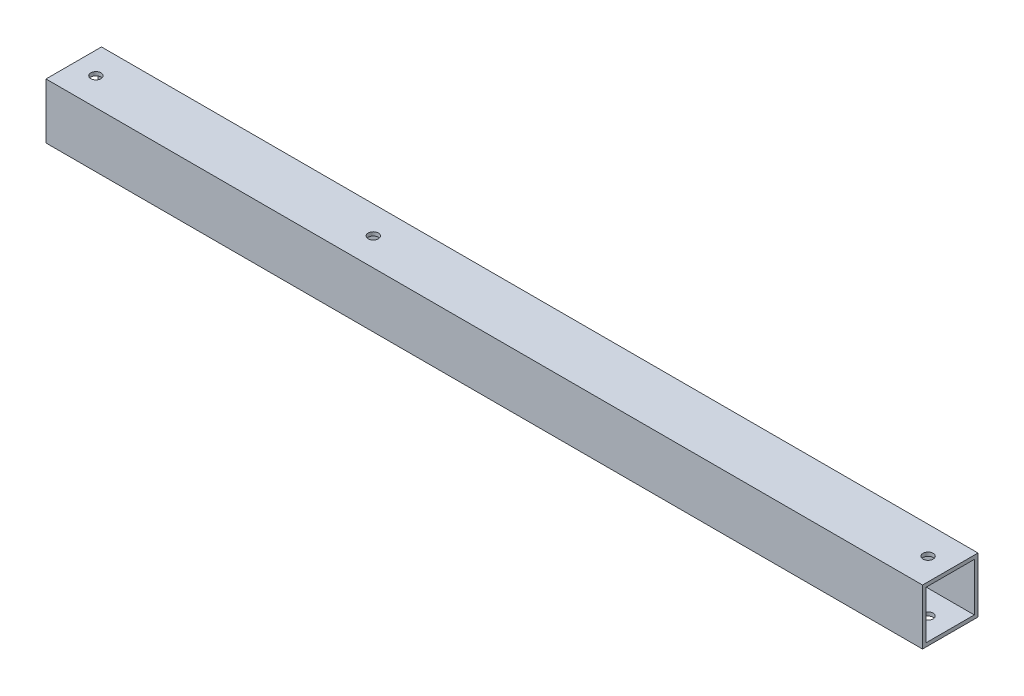
SolidWorks part; units mm, degrees
ref_plane "Front Plane" through (0, 0, 0) normal (0, 0, 1) x (1, 0, 0)
ref_plane "Top Plane" through (0, 0, 0) normal (0, 1, 0) x (1, 0, 0)
ref_plane "Right Plane" through (0, 0, 0) normal (1, 0, 0) x (0, 0, -1)
sketch "Sketch1" plane through (0, 0, 0) normal (1, 0, 0) x (0, 0, -1)
  line L1 (15, 15) -> (-15, 15)
  line L2 (15, 15) -> (15, -15)
  line L3 (15, -15) -> (-15, -15)
  line L4 (-15, 15) -> (-15, -15)
  line L5 (15, 15) -> (-15, -15) construction
  line L6 (15, -15) -> (-15, 15) construction
  line L7 (-13, 13) -> (13, 13)
  line L8 (-13, 13) -> (-13, -13)
  line L9 (-13, -13) -> (13, -13)
  line L10 (13, 13) -> (13, -13)
  line L11 (-13, 13) -> (13, -13) construction
  line L12 (-13, -13) -> (13, 13) construction
  point P0 (0, 0)
  point P5 (0, 0)
  dimension "D1" = 30
  dimension "D2" = 30
  dimension "D3" = 2
extrude "Boss-Extrude1" add sketch "Sketch1" along normal mid plane 474
sketch "Sketch2" plane through (0, 0, 0) normal (0, 1, 0) x (1, 0, 0)
  line L0 (237, 15) -> (237, -15) construction
  circle A0 centre (225, 0) radius 2.75
  dimension "D1" = 5.5
  dimension "D2" = 12
extrude "Cut-Extrude1" cut sketch "Sketch2" against normal through all both and the other way through all
mirror "Mirror1" about plane through (0, 0, 0) normal (1, 0, 0) of "Cut-Extrude1"
sketch "Sketch3" plane through (0, 0, 0) normal (0, 1, 0) x (1, 0, 0)
  line L0 (-225, 0) -> (-75, 0) construction
  circle A0 centre (-75, 0) radius 2.75
  dimension "D2" = 5.5
  dimension "D1" = 150
extrude "Cut-Extrude2" cut sketch "Sketch3" against normal through all both and the other way through all
equation "\"D2@Sketch1\"=\"w\""
equation "\"D1@Sketch1\"=\"w\""
equation "\"t\"= 2"
equation "\"w\"= 30"
equation "\"D3@Sketch1\"=\"t\""
